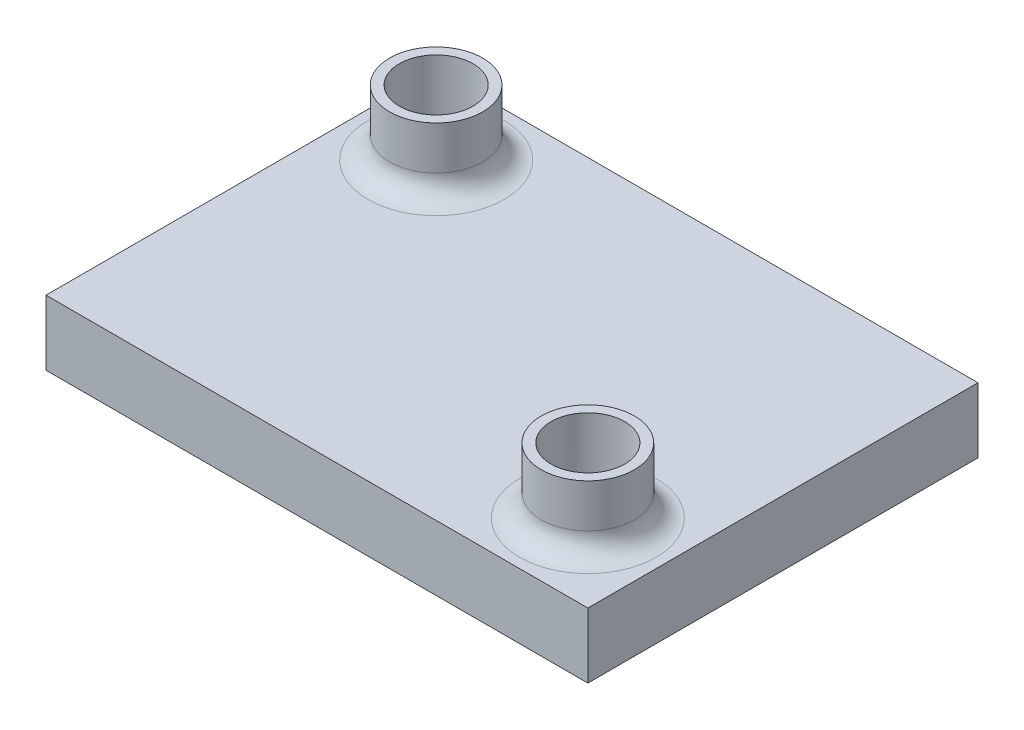
SolidWorks part; units mm, degrees
ref_plane "Front Plane" through (0, 0, 0) normal (0, 0, 1) x (1, 0, 0)
ref_plane "Top Plane" through (0, 0, 0) normal (0, 1, 0) x (1, 0, 0)
ref_plane "Right Plane" through (0, 0, 0) normal (1, 0, 0) x (0, 0, -1)
sketch "Sketch2" plane through (0, 0, 0) normal (0, 1, 0) x (1, 0, 0)
  line L0 (0, 0) -> (12.5, 0) construction
  line L1 (-12.5, 9) -> (12.5, 9)
  line L2 (-12.5, 9) -> (-12.5, -9)
  line L3 (-12.5, -9) -> (12.5, -9)
  line L4 (12.5, 9) -> (12.5, -9)
  line L5 (0, 0) -> (0, 9) construction
  dimension "D1" = 25
  dimension "D2" = 18
extrude "Boss-Extrude1" add sketch "Sketch2" along normal blind 3
sketch "Sketch3" plane through (0, 3, 0) normal (0, 1, 0) x (1, 0, 0)
  line L1 (-12.5, -9) -> (12.5, -9) construction
  line L2 (0, 0) -> (-12.5, 0) construction
  line L3 (-12.5, 9) -> (-12.5, -9) construction
  line L4 (0, 0) -> (0, -9) construction
  line L5 (-8.8999, 5.4) -> (-8.8999, 0) construction
  line L6 (8.8999, -5.4) -> (8.8999, 0) construction
  line L7 (0, 0) -> (12.5, 0) construction
  line L8 (12.5, -9) -> (12.5, 9) construction
  line L9 (12.1, -8.6) -> (-12.1, -8.6) construction
  line L10 (12.1, -8.6) -> (12.1, 8.6) construction
  line L11 (12.1, 8.6) -> (-12.1, 8.6) construction
  line L12 (-12.1, -8.6) -> (-12.1, 8.6) construction
  circle A0 centre (-8.8999, 5.4) radius 1.7
  circle A1 centre (8.8999, -5.4) radius 1.7
  point P13 (0, 0)
  point P22 (0, 0)
  dimension "D1" = 3.4
  dimension "D2" = 17.2
  dimension "D3" = 24.2
  dimension "D4" = 20.82
  dimension "D5" = 14
  dimension "D6" = 14
extrude "Cut-Extrude1" cut sketch "Sketch3" against normal through all
sketch "Sketch4" plane through (0, 3, 0) normal (0, 1, 0) x (1, 0, 0)
  circle A0 centre (-8.8999, 5.4) radius 1.7
  circle A1 centre (-8.8999, 5.4) radius 2.15
  circle A2 centre (-8.8999, 5.4) radius 1.7 construction
  circle A3 centre (8.8999, -5.4) radius 2.15
  circle A4 centre (8.8999, -5.4) radius 1.7
  circle A5 centre (8.8999, -5.4) radius 1.7 construction
  dimension "D1" = 4.3
extrude "Boss-Extrude2" add sketch "Sketch4" along normal blind 3
fillet "Fillet1" radius 1 2 edges at (8.8999, 3, 7.55) (-8.8999, 3, -3.25)
sketch "Sketch5" plane through (0, 0, 0) normal (0, -1, 0) x (1, 0, 0)
  line L0 (12.5, -9) -> (-12.5, -9) construction
  line L1 (10.5453, 2.55) -> (12.1908, 5.4)
  line L2 (12.1908, 5.4) -> (10.5453, 8.25)
  line L3 (10.5453, 8.25) -> (7.2544, 8.25)
  line L4 (7.2544, 8.25) -> (5.609, 5.4)
  line L5 (5.609, 5.4) -> (7.2544, 2.55)
  line L6 (7.2544, 2.55) -> (10.5453, 2.55)
  line L8 (-7.2544, -8.25) -> (-5.609, -5.4)
  line L9 (-5.609, -5.4) -> (-7.2544, -2.55)
  line L10 (-7.2544, -2.55) -> (-10.5453, -2.55)
  line L11 (-10.5453, -2.55) -> (-12.1908, -5.4)
  line L12 (-12.1908, -5.4) -> (-10.5453, -8.25)
  line L13 (-10.5453, -8.25) -> (-7.2544, -8.25)
  circle A0 centre (8.8999, 5.4) radius 2.85 construction
  circle A1 centre (-8.8999, -5.4) radius 2.85 construction
  point P12 (-11.3896, -3.4054)
  dimension "D1" = 5.7
extrude "Cut-Extrude2" cut sketch "Sketch5" against normal blind 2
